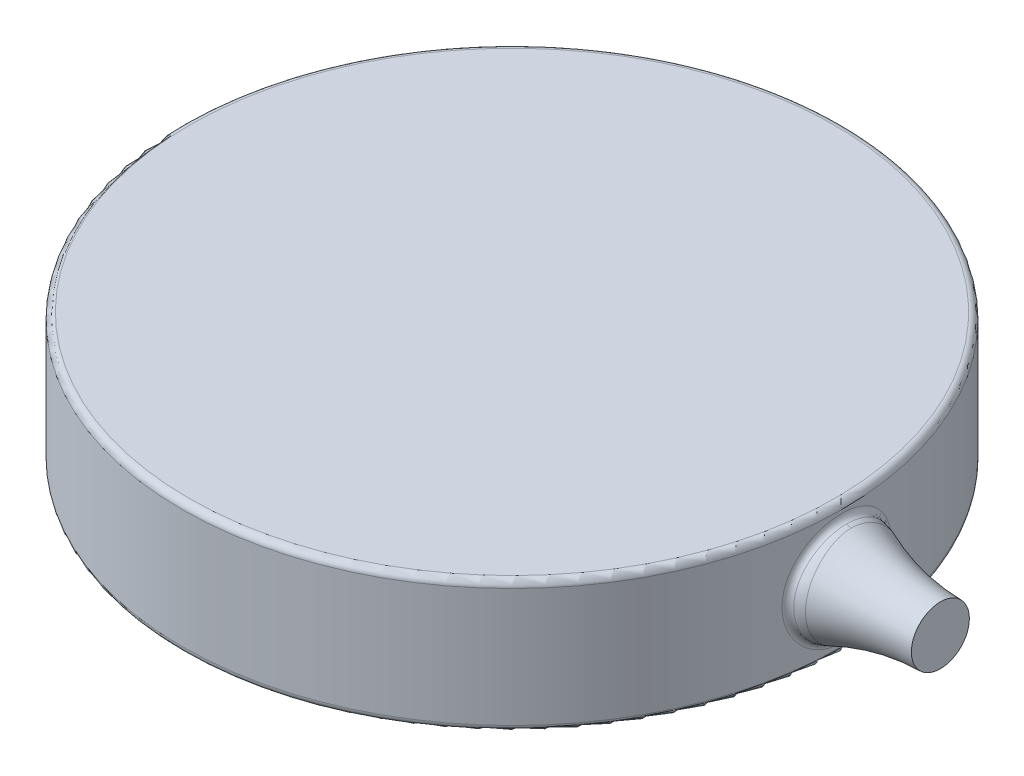
SolidWorks part; units mm, degrees
material "Alloy Steel"
ref_plane "Front Plane" through (0, 0, 0) normal (0, 0, 1) x (1, 0, 0)
ref_plane "Top Plane" through (0, 0, 0) normal (0, 1, 0) x (1, 0, 0)
ref_plane "Right Plane" through (0, 0, 0) normal (1, 0, 0) x (0, 0, -1)
sketch "Sketch1" plane through (0, 0, 0) normal (0, 1, 0) x (1, 0, 0)
  circle A0 centre (0, 0) radius 5
  dimension "D1" = 10
extrude "Boss-Extrude1" add sketch "Sketch1" along normal blind 2
sketch "Sketch2" plane through (0, 0, 0) normal (1, 0, 0) x (0, 0, -1)
  line L0 (0, 0) -> (0, 2) construction
  line L1 (5, 2) -> (-5, 2) construction
  circle A0 centre (0, 1) radius 0.75
  dimension "D1" = 1.5
extrude "Boss-Extrude2" add sketch "Sketch2" along normal blind 6.5
fillet "Fillet2" radius 0.1 3 edges at (4.9461, 1.1631, -0.7321) (0, 0, 5) (0, 2, 5)
sketch "Sketch3" plane through (0, 0, 0) normal (0, 0, 1) x (1, 0, 0)
  line L0 (6.5, 0.25) -> (6.5, 1.75) construction
  line L4 (5.1, 1.75) -> (6.5, 1.75)
  line L5 (6.5, 1.75) -> (6.5, 1.4399)
  spline S0 degree 2 poles (5.1, 1.75) (5.7669, 1.4524) (6.5, 1.4399) knots 0 0 0 1 1 1
revolve "Cut-Revolve1" cut sketch "Sketch3" angle 360 about axis through (6.5, 1, 0) along (-1, 0, 0)
fillet "Fillet3" radius 0.4 4 edges at (5.0296, 0.9144, -0.7451) (5.0296, 0.9144, -0.7451)
equation "\"Diameter\"= 10mm"
equation "\"Height\"= 2mm"
equation "\"D1@Sketch1\"=\"Diameter\""
equation "\"D1@Boss-Extrude1\"=\"Height\""
